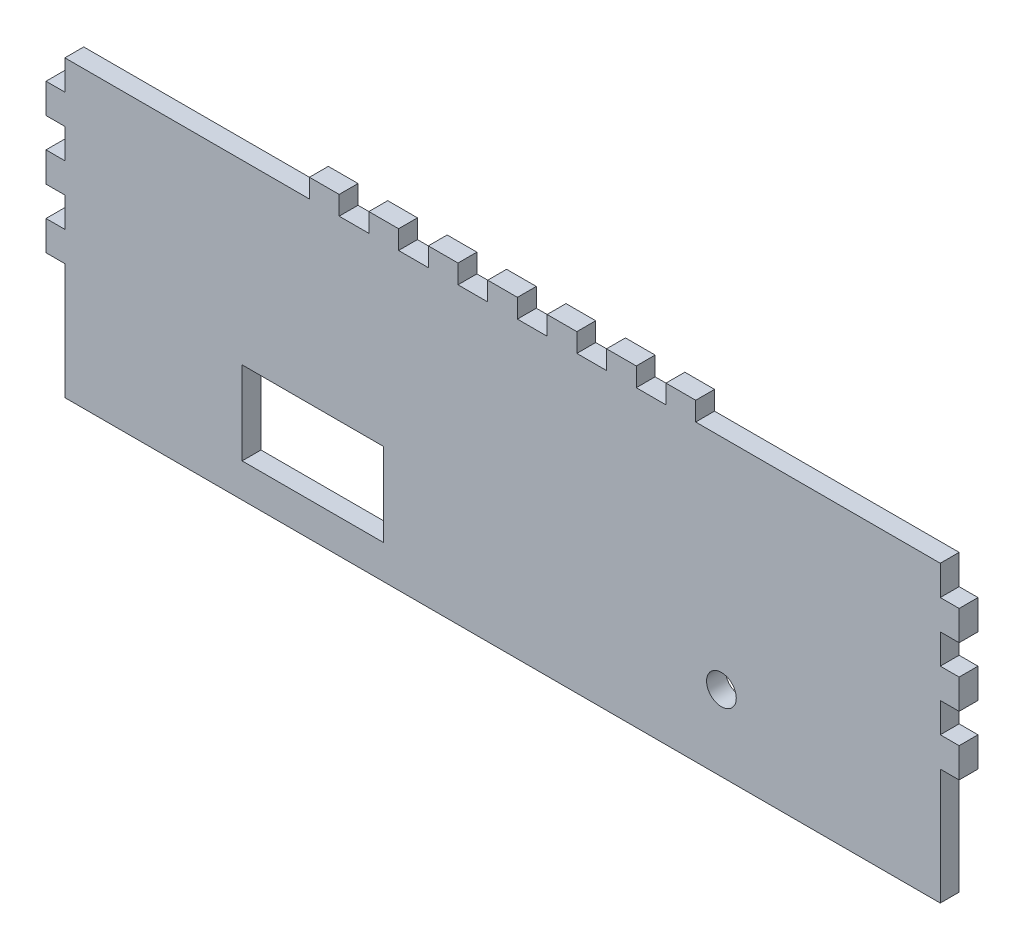
SolidWorks part; units mm, degrees
ref_plane "Front Plane" through (0, 0, 0) normal (0, 0, 1) x (1, 0, 0)
ref_plane "Top Plane" through (0, 0, 0) normal (0, 1, 0) x (1, 0, 0)
ref_plane "Right Plane" through (0, 0, 0) normal (1, 0, 0) x (0, 0, -1)
sketch "Sketch1" plane through (0, 0, 0) normal (0, 0, 1) x (1, 0, 0)
  line L0 (-147.32, -36.83) -> (0, -36.83) construction
  line L1 (-147.32, 0) -> (-106.16, 0)
  line L2 (0, 0) -> (0, -5)
  line L3 (0, -49.53) -> (-147.32, -49.53)
  line L4 (-147.32, 0) -> (-147.32, -5)
  line L6 (-117.49, -29.83) -> (-93.6775, -29.83)
  line L7 (-51.16, 0) -> (-46.16, 0)
  line L8 (-46.16, 0) -> (-46.16, 3.175)
  line L9 (-46.16, 3.175) -> (-41.16, 3.175)
  line L10 (-117.49, -29.83) -> (-117.49, -43.83)
  line L11 (-117.49, -43.83) -> (-93.6775, -43.83)
  line L12 (-93.6775, -29.83) -> (-93.6775, -43.83)
  line L16 (-106.16, 0) -> (-106.16, 3.175)
  line L17 (-106.16, 3.175) -> (-101.16, 3.175)
  line L18 (-101.16, 0) -> (-101.16, 3.175)
  line L19 (-101.16, 0) -> (-96.16, 0)
  line L20 (-96.16, 0) -> (-96.16, 3.175)
  line L21 (-96.16, 3.175) -> (-91.16, 3.175)
  line L22 (-91.16, 0) -> (-91.16, 3.175)
  line L23 (-91.16, 0) -> (-86.16, 0)
  line L24 (-86.16, 0) -> (-86.16, 3.175)
  line L25 (-86.16, 3.175) -> (-81.16, 3.175)
  line L26 (-81.16, 0) -> (-81.16, 3.175)
  line L27 (-81.16, 0) -> (-76.16, 0)
  line L28 (-76.16, 0) -> (-76.16, 3.175)
  line L29 (-76.16, 3.175) -> (-71.16, 3.175)
  line L30 (-71.16, 0) -> (-71.16, 3.175)
  line L31 (-71.16, 0) -> (-66.16, 0)
  line L32 (-66.16, 0) -> (-66.16, 3.175)
  line L33 (-66.16, 3.175) -> (-61.16, 3.175)
  line L34 (-61.16, 0) -> (-61.16, 3.175)
  line L35 (-61.16, 0) -> (-56.16, 0)
  line L36 (-56.16, 0) -> (-56.16, 3.175)
  line L37 (-56.16, 3.175) -> (-51.16, 3.175)
  line L38 (-51.16, 0) -> (-51.16, 3.175)
  line L39 (-41.16, 3.175) -> (-41.16, 0)
  line L40 (-41.16, 0) -> (0, 0)
  line L44 (-147.32, -10) -> (-147.32, -15)
  line L45 (-147.32, -5) -> (-150.495, -5)
  line L47 (-147.32, -15) -> (-150.495, -15)
  line L48 (-147.32, -10) -> (-150.495, -10)
  line L49 (-150.495, -5) -> (-150.495, -10)
  line L50 (-150.495, -15) -> (-150.495, -20)
  line L51 (-147.32, -20) -> (-150.495, -20)
  line L52 (-147.32, -20) -> (-147.32, -25)
  line L53 (-147.32, -25) -> (-150.495, -25)
  line L54 (-150.495, -25) -> (-150.495, -30)
  line L55 (-147.32, -30) -> (-150.495, -30)
  line L56 (-147.32, -30) -> (-147.32, -49.53)
  line L59 (-73.66, 19.832) -> (-73.66, -118.892) construction
  line L60 (3.175, -25) -> (3.175, -30)
  line L61 (3.175, -15) -> (3.175, -20)
  line L62 (3.175, -5) -> (3.175, -10)
  line L63 (3.175, -5) -> (0, -5)
  line L64 (3.175, -10) -> (0, -10)
  line L65 (3.175, -15) -> (0, -15)
  line L66 (3.175, -20) -> (0, -20)
  line L67 (3.175, -25) -> (0, -25)
  line L68 (3.175, -30) -> (0, -30)
  line L69 (0, -20) -> (0, -25)
  line L70 (0, -30) -> (0, -49.53)
  line L71 (0, -10) -> (0, -15)
  circle A1 centre (-36.83, -36.83) radius 2.5
  point P7 (-110.49, -36.83)
  point P72 (-73.66, -49.53)
  dimension "D3" = 7
  dimension "D5" = 12.7
  dimension "D6" = 3.175
  dimension "D1" = 5
  dimension "D2" = 7
  dimension "D4" = 36.83
  dimension "D7" = 36.83
  dimension "D9" = 5
  dimension "D10" = 5
  dimension "D12" = 147.32
  dimension "D13" = 16.8125
  dimension "D8" = 3.175
  dimension "D14" = 36.83
  dimension "D15" = 7
  dimension "D17" = 5
  dimension "D18" = 5
  dimension "D11" = 3
extrude "Boss-Extrude1" add sketch "Sketch1" along normal blind 3.175
sketch "Sketch2" plane through (0, 0, 3.175) normal (0, 0, 1) x (1, 0, 0)
